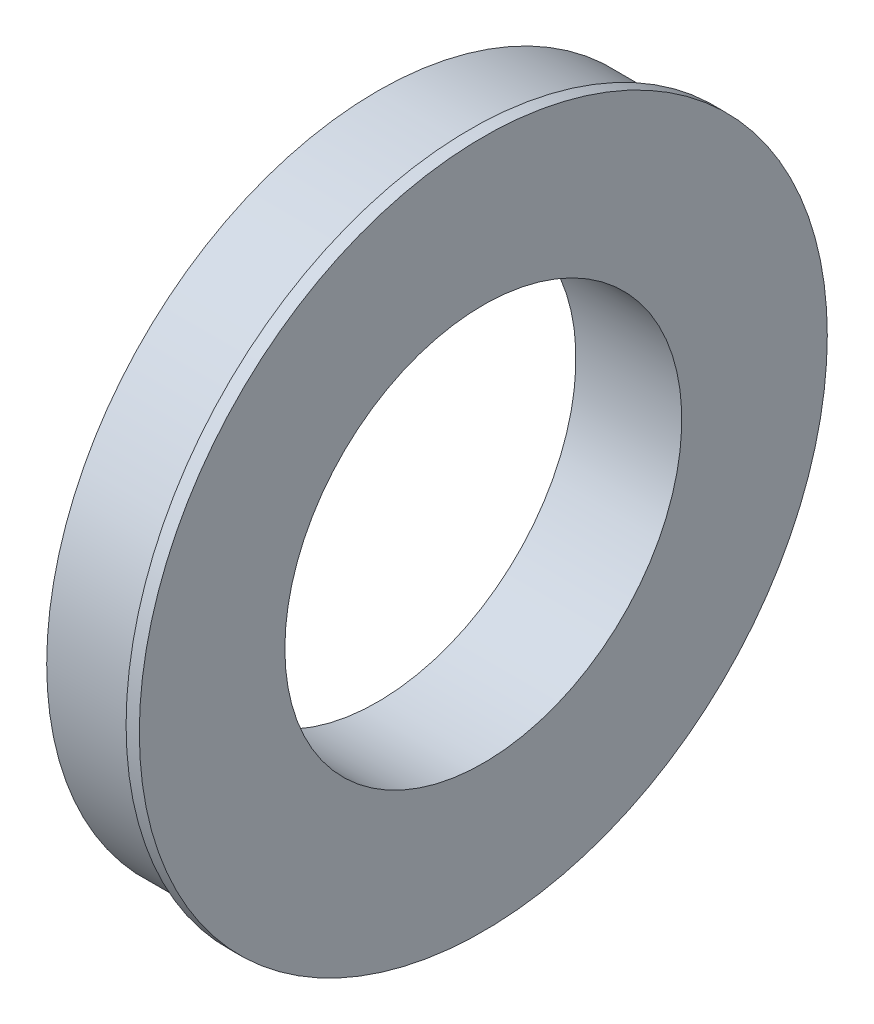
SolidWorks part; units mm, degrees
ref_plane "Front Plane" through (0, 0, 0) normal (0, 0, 1) x (1, 0, 0)
ref_plane "Top Plane" through (0, 0, 0) normal (0, 1, 0) x (1, 0, 0)
ref_plane "Right Plane" through (0, 0, 0) normal (1, 0, 0) x (0, 0, -1)
sketch "Sketch1" plane through (0, 0, 0) normal (1, 0, 0) x (0, 0, -1)
  circle A0 centre (0, 0) radius 63.5
  circle A1 centre (0, 0) radius 38.1
  dimension "D1" = 127
  dimension "D2" = 76.2
extrude "Boss-Extrude1" add sketch "Sketch1" along normal mid plane 19.05
sketch "Sketch2" plane through (9.525, 0, 0) normal (1, 0, 0) x (0, 0, -1)
  circle A0 centre (0, 0) radius 38.1 construction
  circle A1 centre (0, 0) radius 38.1
  circle A2 centre (0, 0) radius 66.04
  dimension "D1" = 132.08
extrude "Boss-Extrude2" add sketch "Sketch2" along normal mid plane 2.54
